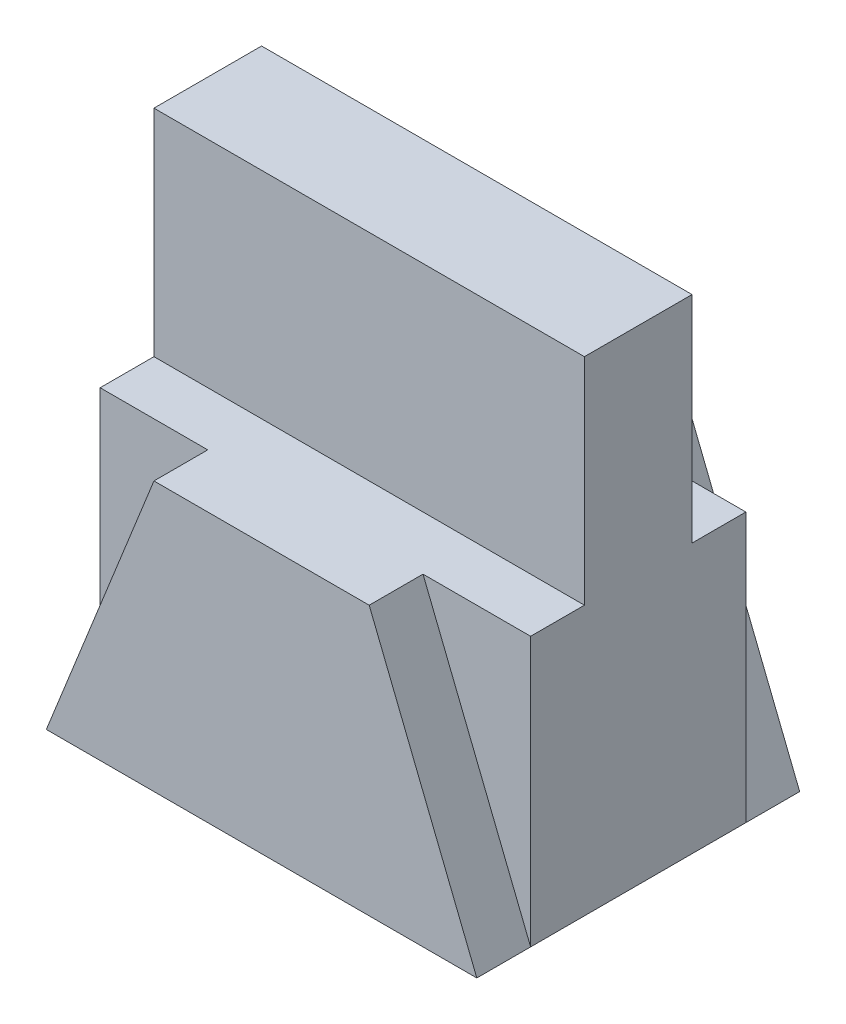
SolidWorks part; units mm, degrees
ref_plane "Alzado" through (0, 0, 0) normal (0, 0, 1) x (1, 0, 0)
ref_plane "Planta" through (0, 0, 0) normal (0, 1, 0) x (1, 0, 0)
ref_plane "Vista lateral" through (0, 0, 0) normal (1, 0, 0) x (0, 0, -1)
sketch "Croquis1" plane through (0, 0, 0) normal (1, 0, 0) x (0, 0, -1)
  line L0 (-15, 0) -> (15, 0)
  line L1 (15, 0) -> (15, 25)
  line L2 (15, 25) -> (5, 25)
  line L3 (5, 25) -> (5, 45)
  line L4 (5, 45) -> (-5, 45)
  line L5 (-5, 45) -> (-5, 25)
  line L6 (-5, 25) -> (-15, 25)
  line L7 (-15, 25) -> (-15, 0)
  point P3 (0, 0)
  point P10 (0, 45)
  dimension "D1" = 45
  dimension "D2" = 25
  dimension "D3" = 10
  dimension "D4" = 30
extrude "Saliente-Extruir1" add sketch "Croquis1" along normal mid plane 40
sketch "Croquis3" plane through (0, 0, 15) normal (0, 0, 1) x (1, 0, 0)
  line L0 (-20, 25) -> (-10, 25)
  line L1 (20, 25) -> (-20, 25) construction
  line L2 (-10, 25) -> (-20, 0)
  line L3 (-20, 0) -> (-20, 25)
  line L4 (10, 25) -> (20, 25)
  line L5 (20, 25) -> (20, 0)
  line L6 (20, 0) -> (10, 25)
  point P10 (0, 0)
  dimension "D1" = 20
extrude "Cortar-Extruir1" cut sketch "Croquis3" against normal blind 5
mirror "Simetría1" about plane through (0, 0, 0) normal (0, 0, 1) of "Cortar-Extruir1"
